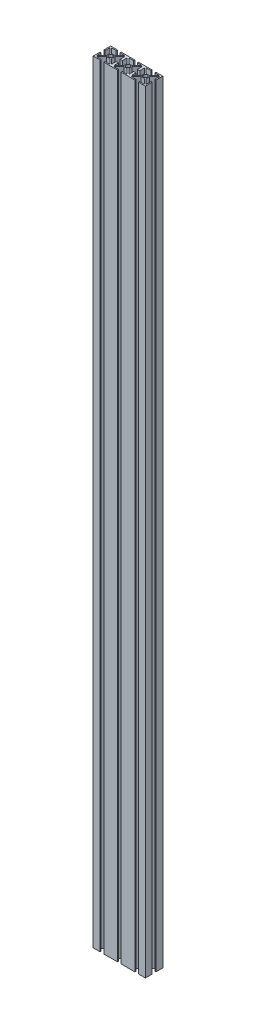
SolidWorks part; units mm, degrees
ref_plane "Front Plane" through (0, 0, 0) normal (0, 0, 1) x (1, 0, 0)
ref_plane "Top Plane" through (0, 0, 0) normal (0, 1, 0) x (1, 0, 0)
ref_plane "Right Plane" through (0, 0, 0) normal (1, 0, 0) x (0, 0, -1)
sketch "Sketch3" plane through (0, 0, 0) normal (0, 1, 0) x (1, 0, 0)
  line L0 (-19.5, 17.3787) -> (-6.5, 4.3787)
  line L5 (-22.5, -22.5) -> (22.5, 22.5) construction
  line L6 (-22.5, 22.5) -> (22.5, -22.5) construction
  line L7 (-17.3787, 19.5) -> (-4.3787, 6.5)
  line L8 (-17.3787, -19.5) -> (-4.3787, -6.5)
  line L9 (-19.5, -17.3787) -> (-6.5, -4.3787)
  line L10 (-22.5, 22.5) -> (-5, 22.5)
  line L11 (-22.5, 22.5) -> (-22.5, 5)
  line L12 (-19.5, 17.3787) -> (-19.5, 5)
  line L13 (-17.3787, 19.5) -> (-5, 19.5)
  line L14 (-22.5, 5) -> (-19.5, 5)
  line L15 (-5, 19.5) -> (-5, 22.5)
  line L16 (4.3787, -6.5) -> (17.3787, -19.5)
  line L17 (4.3787, -6.5) -> (-4.3787, -6.5)
  line L18 (6.5, -4.3787) -> (6.5, 4.3787)
  line L19 (4.3787, 6.5) -> (-4.3787, 6.5)
  line L20 (-6.5, -4.3787) -> (-6.5, 4.3787)
  line L21 (6.5, -6.5) -> (-6.5, 6.5) construction
  line L22 (6.5, 6.5) -> (-6.5, -6.5) construction
  line L23 (-40.6213, 6.5) -> (-27.6213, 19.5)
  line L24 (-28.2242, 0) -> (83.542, 0) construction
  line L25 (0, 28.4091) -> (0, -29.3164) construction
  line L26 (19.5, 17.3787) -> (19.5, 5)
  line L27 (22.5, 5) -> (19.5, 5)
  line L28 (22.5, 22.5) -> (22.5, 5)
  line L29 (5, 19.5) -> (5, 22.5)
  line L30 (17.3787, 19.5) -> (5, 19.5)
  line L31 (22.5, 22.5) -> (5, 22.5)
  line L32 (22.5, -22.5) -> (5, -22.5)
  line L33 (17.3787, -19.5) -> (5, -19.5)
  line L34 (5, -19.5) -> (5, -22.5)
  line L35 (22.5, -22.5) -> (22.5, -5)
  line L36 (22.5, -5) -> (19.5, -5)
  line L37 (19.5, -17.3787) -> (19.5, -5)
  line L38 (-22.5, -5) -> (-19.5, -5)
  line L39 (-19.5, -17.3787) -> (-19.5, -5)
  line L40 (-22.5, -22.5) -> (-22.5, -5)
  line L41 (-5, -19.5) -> (-5, -22.5)
  line L42 (-17.3787, -19.5) -> (-5, -19.5)
  line L43 (-22.5, -22.5) -> (-5, -22.5)
  line L44 (-27.6213, 19.5) -> (-40, 19.5)
  line L45 (-40, 19.5) -> (-40, 22.5)
  line L46 (4.3787, 6.5) -> (17.3787, 19.5)
  line L47 (-22.5, 22.5) -> (-40, 22.5)
  line L48 (6.5, 4.3787) -> (19.5, 17.3787)
  line L49 (-22.5, 22.5) -> (-22.5, 5)
  line L50 (6.5, -4.3787) -> (19.5, -17.3787)
  line L51 (-22.5, 5) -> (-25.5, 5)
  line L52 (-25.5, 17.3787) -> (-25.5, 5)
  line L53 (-38.5, 4.3787) -> (-25.5, 17.3787)
  line L54 (-38.5, -4.3787) -> (-38.5, 4.3787)
  line L55 (-38.5, -4.3787) -> (-25.5, -17.3787)
  line L56 (-25.5, -17.3787) -> (-25.5, -5)
  line L57 (-22.5, -5) -> (-25.5, -5)
  line L58 (-22.5, -22.5) -> (-22.5, -5)
  line L59 (-22.5, -22.5) -> (-40, -22.5)
  line L60 (-40, -19.5) -> (-40, -22.5)
  line L61 (-27.6213, -19.5) -> (-40, -19.5)
  line L62 (-40.6213, -6.5) -> (-27.6213, -19.5)
  line L63 (-40.6213, -6.5) -> (-49.3787, -6.5)
  line L64 (-62.3787, -19.5) -> (-49.3787, -6.5)
  line L65 (-62.3787, -19.5) -> (-50, -19.5)
  line L66 (-50, -19.5) -> (-50, -22.5)
  line L67 (-67.5, -22.5) -> (-50, -22.5)
  line L68 (-67.5, -22.5) -> (-67.5, -5)
  line L69 (-67.5, -5) -> (-64.5, -5)
  line L70 (-64.5, -17.3787) -> (-64.5, -5)
  line L71 (-64.5, -17.3787) -> (-51.5, -4.3787)
  line L72 (-51.5, -4.3787) -> (-51.5, 4.3787)
  line L73 (-64.5, 17.3787) -> (-51.5, 4.3787)
  line L74 (-64.5, 17.3787) -> (-64.5, 5)
  line L75 (-67.5, 5) -> (-64.5, 5)
  line L76 (-67.5, 22.5) -> (-67.5, 5)
  line L77 (-67.5, 22.5) -> (-50, 22.5)
  line L78 (-50, 19.5) -> (-50, 22.5)
  line L79 (-62.3787, 19.5) -> (-50, 19.5)
  line L80 (-62.3787, 19.5) -> (-49.3787, 6.5)
  line L81 (-40.6213, 6.5) -> (-49.3787, 6.5)
  line L82 (-85.6213, 6.5) -> (-72.6213, 19.5)
  line L83 (-72.6213, 19.5) -> (-85, 19.5)
  line L84 (-85, 19.5) -> (-85, 22.5)
  line L85 (-67.5, 22.5) -> (-85, 22.5)
  line L86 (-67.5, 22.5) -> (-67.5, 5)
  line L87 (-67.5, 5) -> (-70.5, 5)
  line L88 (-70.5, 17.3787) -> (-70.5, 5)
  line L89 (-83.5, 4.3787) -> (-70.5, 17.3787)
  line L90 (-83.5, -4.3787) -> (-83.5, 4.3787)
  line L91 (-83.5, -4.3787) -> (-70.5, -17.3787)
  line L92 (-70.5, -17.3787) -> (-70.5, -5)
  line L93 (-67.5, -5) -> (-70.5, -5)
  line L94 (-67.5, -22.5) -> (-67.5, -5)
  line L95 (-67.5, -22.5) -> (-85, -22.5)
  line L96 (-85, -19.5) -> (-85, -22.5)
  line L97 (-72.6213, -19.5) -> (-85, -19.5)
  line L98 (-85.6213, -6.5) -> (-72.6213, -19.5)
  line L99 (-85.6213, -6.5) -> (-94.3787, -6.5)
  line L100 (-107.3787, -19.5) -> (-94.3787, -6.5)
  line L101 (-107.3787, -19.5) -> (-95, -19.5)
  line L102 (-95, -19.5) -> (-95, -22.5)
  line L103 (-112.5, -22.5) -> (-95, -22.5)
  line L104 (-112.5, -22.5) -> (-112.5, -5)
  line L105 (-112.5, -5) -> (-109.5, -5)
  line L106 (-109.5, -17.3787) -> (-109.5, -5)
  line L107 (-109.5, -17.3787) -> (-96.5, -4.3787)
  line L108 (-96.5, -4.3787) -> (-96.5, 4.3787)
  line L109 (-109.5, 17.3787) -> (-96.5, 4.3787)
  line L110 (-109.5, 17.3787) -> (-109.5, 5)
  line L111 (-112.5, 5) -> (-109.5, 5)
  line L112 (-112.5, 22.5) -> (-112.5, 5)
  line L113 (-112.5, 22.5) -> (-95, 22.5)
  line L114 (-95, 19.5) -> (-95, 22.5)
  line L115 (-107.3787, 19.5) -> (-95, 19.5)
  line L116 (-107.3787, 19.5) -> (-94.3787, 6.5)
  line L117 (-85.6213, 6.5) -> (-94.3787, 6.5)
  line L118 (4.3787, 6.5) -> (-40.6213, 6.5) construction
  circle A0 centre (0, 0) radius 5
  circle A1 centre (-45, 0) radius 5
  circle A2 centre (-90, 0) radius 5
  point P0 (0, 0)
  dimension "D1" = 45
  dimension "D2" = 3
extrude "Boss-Extrude1" add sketch "Sketch3" along normal blind 2000 contours L82 L117 L116 L115 L114 L113 L112 L111 L110 L109 L108 L107 L106 L105 L104 L103 L102 L101 L100 L99 L98 L97 L96 L95 L68 L93 L92 L91 L90 L89 L88 L87 L76 L85 L84 L83 A2 | L23 L81 L80 L79 L78 L77 L76 L75 L74 L73 L72 L71 L70 L69 L68 L67 L66 L65 L64 L63 L62 L61 L60 L59 L40 L57 L56 L55 L54 L53 L52 L51 L11 L47 L45 L44 A1 | L50 L18 L48 L26 L27 L28 L31 L29 L30 L46 L19 L7 L13 L15 L10 L11 L14 L12 L0 L20 L9 L39 L38 L40 L43 L41 L42 L8 L17 L16 L33 L34 L32 L35 L36 L37 A0
